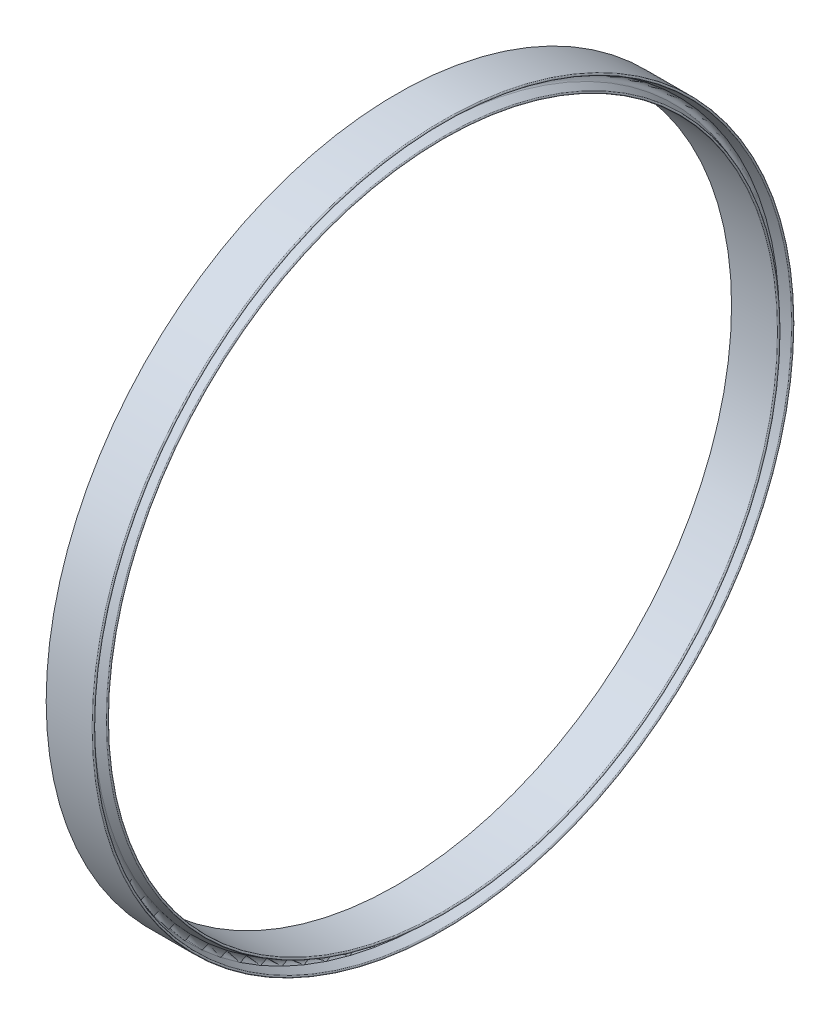
SolidWorks part; units mm, degrees
material "PP Copolymer"
ref_plane "Ön Düzlem" through (0, 0, 0) normal (0, 0, 1) x (1, 0, 0)
ref_plane "Üst Düzlem" through (0, 0, 0) normal (0, 1, 0) x (1, 0, 0)
ref_plane "Sağ Düzlem" through (0, 0, 0) normal (1, 0, 0) x (0, 0, -1)
sketch "Sketch1" plane through (0, 0, 0) normal (0, 0, 1) x (1, 0, 0)
  line L0 (-79.1226, 0) -> (82.6695, 0) construction
  line L1 (-62.7524, -33) -> (-58.4338, -33)
  line L2 (-58.4338, -31.5) -> (-62.7524, -31.5)
  line L3 (-62.7524, -31.5) -> (-62.7524, -33)
  line L4 (-58.405, -31.6958) -> (-59.2946, -31.9627)
  line L5 (-59.2946, -32.5373) -> (-58.405, -32.8042)
  arc A0 (-59.2946, -31.9627) -> (-59.2946, -32.5373) centre (-59.2084, -32.25) ccw
  arc A1 (-58.4338, -31.5) -> (-58.405, -31.6958) centre (-58.4338, -31.6) cw
  arc A2 (-58.4338, -33) -> (-58.405, -32.8042) centre (-58.4338, -32.9) ccw
  point P12 (-57.7524, -31.5)
  point P15 (-57.7524, -33)
  dimension "D5" = 0.3
  dimension "D6" = 0.1
  dimension "D1" = 33
  dimension "D2" = 31.5
  dimension "D3" = 5
  dimension "D4" = 5
revolve "Revolve1" add sketch "Sketch1" angle 360 about L0
